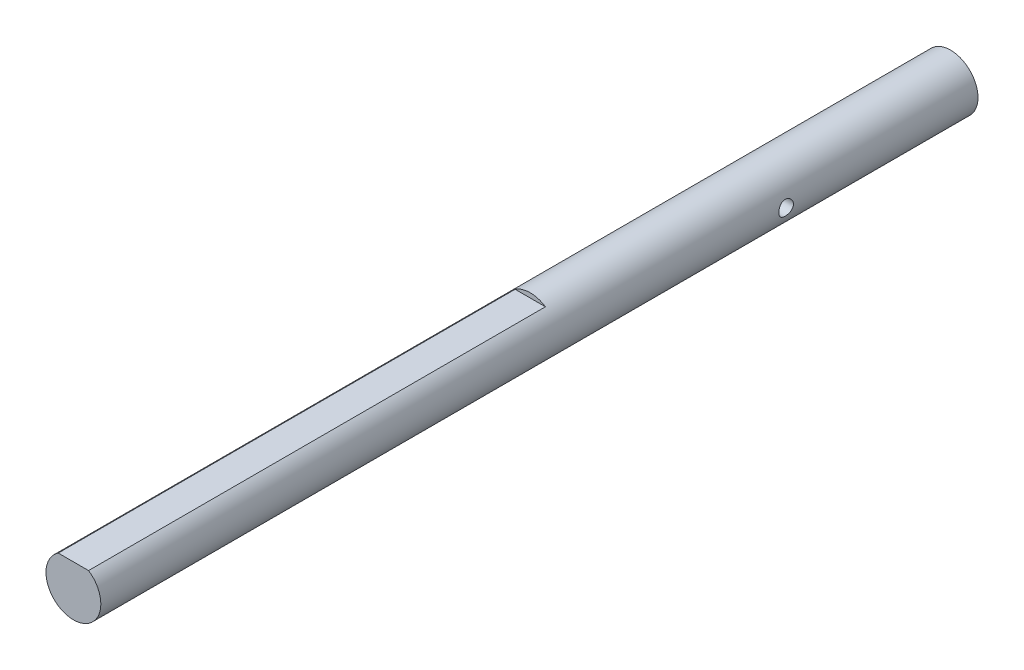
SolidWorks part; units mm, degrees
material "A-1"
ref_plane "Front Plane" through (0, 0, 0) normal (0, 0, 1) x (1, 0, 0)
ref_plane "Top Plane" through (0, 0, 0) normal (0, 1, 0) x (1, 0, 0)
ref_plane "Right Plane" through (0, 0, 0) normal (1, 0, 0) x (0, 0, -1)
sketch "Sketch1" plane through (0, 0, 0) normal (0, 0, 1) x (1, 0, 0)
  circle A0 centre (0, 0) radius 9.525
  dimension "D1" = 19.05
extrude "Boss-Extrude1" add sketch "Sketch1" against normal blind 304.8
sketch "Sketch3" plane through (0, 0, 0) normal (0, 0, 1) x (1, 0, 0)
  line L0 (0, -9.525) -> (6.1064, -9.525) construction
  line L1 (-11.6498, 14.3261) -> (11.7943, 14.3261)
  line L2 (-11.6498, 14.3261) -> (-11.6498, 7.9375)
  line L3 (-11.6498, 7.9375) -> (11.7943, 7.9375)
  line L4 (11.7943, 14.3261) -> (11.7943, 7.9375)
  line L5 (0, -10.4775) -> (0, 10.4775) construction
  circle A1 centre (0, 0) radius 9.525 construction
  dimension "D1" = 17.4625
extrude "Cut-Extrude1" cut sketch "Sketch3" against normal blind 158.75
sketch "Sketch8" plane through (0, 0, 0) normal (1, 0, 0) x (0, 0, -1)
  line L0 (10.4775, 0) -> (-10.4775, 0) construction
  line L1 (304.8, -9.525) -> (304.8, 9.525) construction
  circle A0 centre (238.125, 0) radius 2.54
  dimension "D1" = 5.08
  dimension "D2" = 66.675
extrude "Cut-Extrude2" cut sketch "Sketch8" against normal through all both and the other way through all
